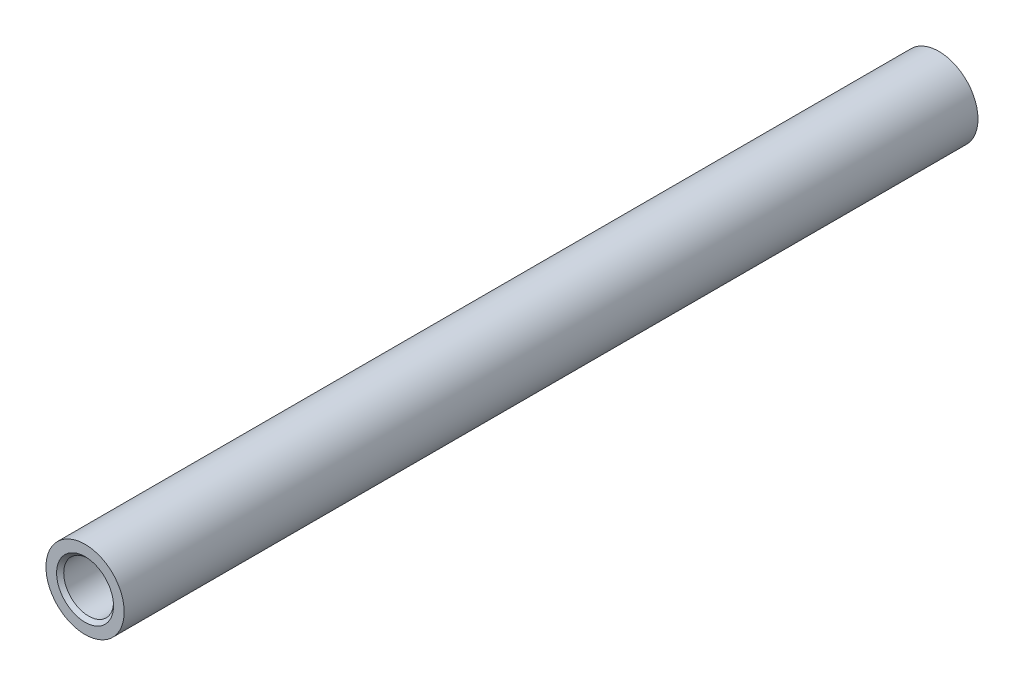
SolidWorks part; units mm, degrees
material "1.0545 (S355N)"
ref_plane "Płaszczyzna przednia" through (0, 0, 0) normal (0, 0, 1) x (1, 0, 0)
ref_plane "Płaszczyzna górna" through (0, 0, 0) normal (0, 1, 0) x (1, 0, 0)
ref_plane "Płaszczyzna prawa" through (0, 0, 0) normal (1, 0, 0) x (0, 0, -1)
sketch "Szkic1" plane through (0, 0, 0) normal (0, 0, 1) x (1, 0, 0)
  circle A0 centre (0, 0) radius 11
  circle A1 centre (0, 0) radius 7
  dimension "D1" = 22
  dimension "D2" = 4
extrude "Dodanie-wyciągnięcie1" add sketch "Szkic1" along normal mid plane 240
sketch "Szkic2" plane through (0, 0, -120) normal (0, 0, -1) x (-1, 0, 0)
  circle A0 centre (0, 0) radius 8
  circle A1 centre (0, 0) radius 7 construction
  dimension "D1" = 1
extrude "Wytnij-wyciągnięcie1" cut sketch "Szkic2" against normal blind 50
chamfer "Sfazowanie1" distance 1 angle 45 1 edges at (7, 0, 120)
